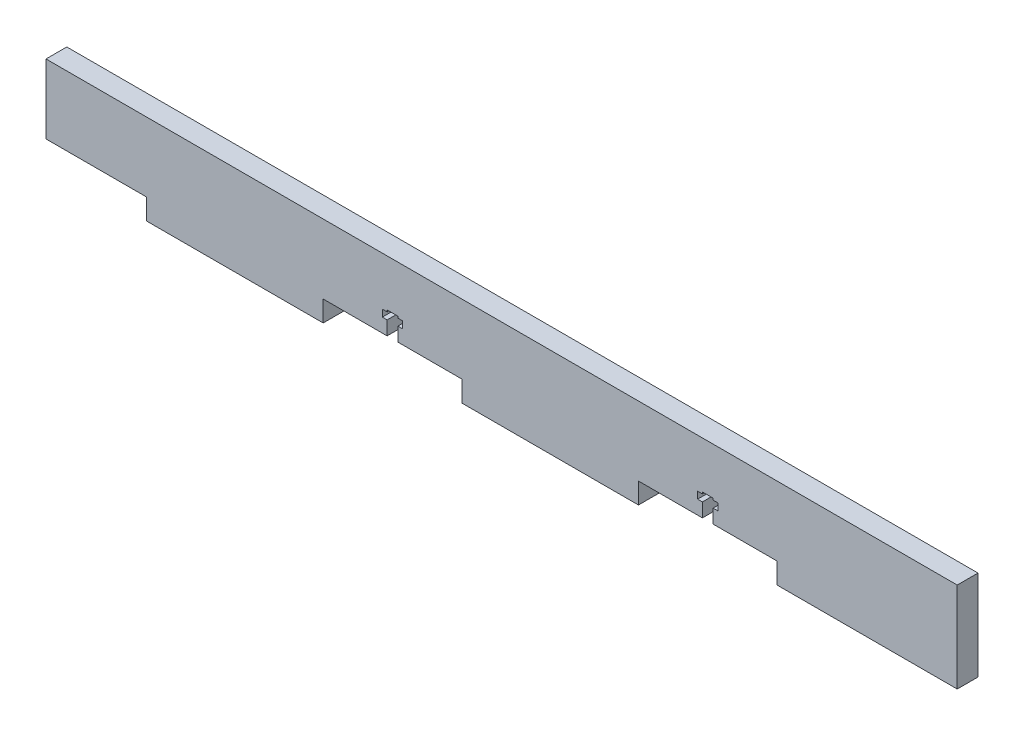
SolidWorks part; units mm, degrees
ref_plane "Płaszczyzna przednia" through (0, 0, 0) normal (0, 0, 1) x (1, 0, 0)
ref_plane "Płaszczyzna górna" through (0, 0, 0) normal (0, 1, 0) x (1, 0, 0)
ref_plane "Płaszczyzna prawa" through (0, 0, 0) normal (1, 0, 0) x (0, 0, -1)
sketch "Szkic1" plane through (0, 0, 0) normal (0, 0, 1) x (1, 0, 0)
  line L0 (-879.9, -6) -> (-615.9, -6)
  line L1 (-879.9, -6) -> (-879.9, 20)
  line L2 (-615.9, -6) -> (-615.9, 20)
  line L3 (-879.9, 20) -> (-615.9, 20)
  dimension "D1" = 26
  dimension "D2" = 264
extrude "Dodanie-wyciągnięcie1" add sketch "Szkic1" against normal blind 6
sketch "Szkic5" plane through (0, 0, 0) normal (0, 0, 1) x (1, 0, 0)
  line L0 (-879.9, 20) -> (-879.9, -6) construction
  line L1 (-889.9, 0) -> (-889.9, -6)
  line L5 (-849.9, 0) -> (-889.9, 0)
  line L6 (-849.9, 0) -> (-849.9, -6)
  line L7 (-849.9, -6) -> (-889.9, -6)
  dimension "D1" = 30
  dimension "D2" = 40
  dimension "D3" = 6
extrude "Wytnij-wyciągnięcie3" cut sketch "Szkic5" against normal blind 6
pattern_linear "Szyk liniowy1" count 3 spacing 91 along (1, 0, 0) of "Wytnij-wyciągnięcie3"
sketch "Szkic6" plane through (0, 0, 0) normal (0, 0, 1) x (1, 0, 0)
  line L0 (-849.9, 0) -> (-879.9, 0) construction
  line L1 (-777.35, 0) -> (-780.45, 0)
  line L2 (-777.35, 0) -> (-777.35, 4)
  line L3 (-777.35, 6.5) -> (-780.45, 6.5)
  line L4 (-780.45, 0) -> (-780.45, 4)
  line L5 (-777.35, 6) -> (-777.35, 6.5)
  line L6 (-775.975, 6) -> (-777.35, 6)
  line L7 (-775.975, 6) -> (-775.975, 4)
  line L8 (-775.975, 4) -> (-777.35, 4)
  line L9 (-781.825, 6) -> (-781.825, 4)
  line L10 (-780.45, 4) -> (-781.825, 4)
  line L11 (-780.45, 6) -> (-781.825, 6)
  line L12 (-780.45, 6) -> (-780.45, 6.5)
  line L14 (-798.9, 0) -> (-798.9, -6) construction
  point P14 (-778.9, 0)
  dimension "D1" = 6.5
  dimension "D2" = 0.5
  dimension "D3" = 5.85
  dimension "D4" = 1.375
  dimension "D5" = 3.1
  dimension "D6" = 2
  dimension "D7" = 20
extrude "Wytnij-wyciągnięcie4" cut sketch "Szkic6" against normal blind 6
pattern_linear "Szyk liniowy2" count 2 spacing 91 along (1, 0, 0) of "Wytnij-wyciągnięcie4"
other "Przenieś ścianę1" face at (-879.9, 10, -3) parameters "D1"=1
equation "\"tolerancja_wpusy\"=0.2"
equation "\"dlugosc_wpustu_duzy\"=20"
equation "\"srednica_otworu_M3\"=3.1"
equation "\"szerokosc_nogi_T\"=3.1"
equation "\"dlugosc_T_30\"=11"
equation "\"grubosc_na_nakretke_kwadrat\"=2"
equation "\"szerokosc_na_nakretke_kwadrat\"=5.85"
equation "\"wyokosc_nadstawki_T\"=0.5"
equation "\"D2@Szkic6\" = \"wyokosc_nadstawki_T\""
equation "\"D3@Szkic6\"=\"szerokosc_na_nakretke_kwadrat\""
equation "\"D4@Szkic6\"=(\"szerokosc_na_nakretke_kwadrat\"-\"szerokosc_nogi_T\")/2"
equation "\"D6@Szkic6\"=\"grubosc_na_nakretke_kwadrat\""
